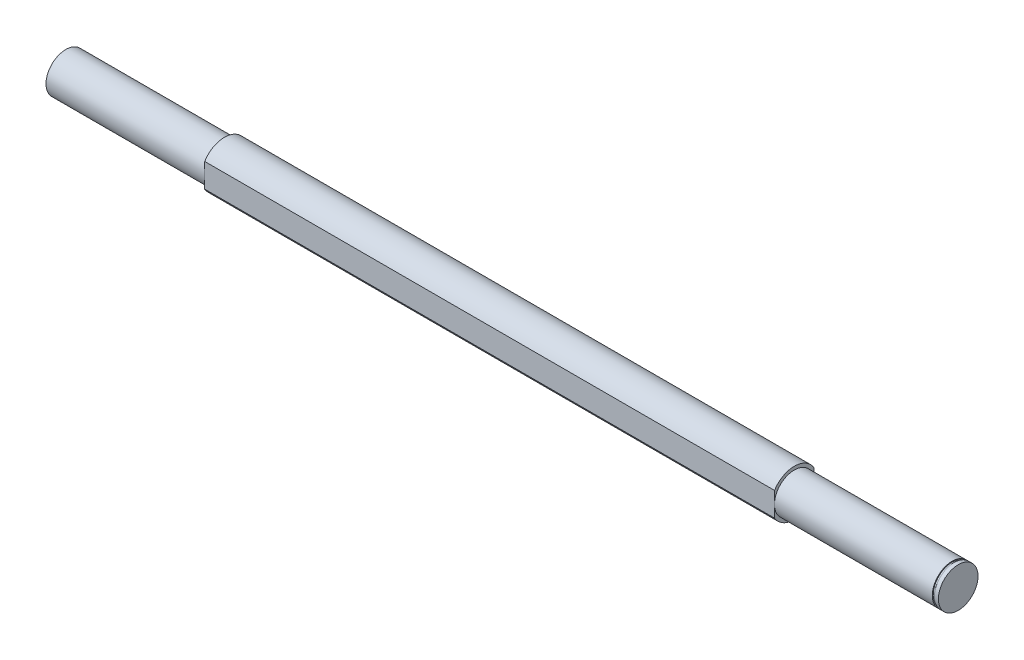
SolidWorks part; units mm, degrees
ref_plane "Ön Düzlem" through (0, 0, 0) normal (0, 0, 1) x (1, 0, 0)
ref_plane "Üst Düzlem" through (0, 0, 0) normal (0, 1, 0) x (1, 0, 0)
ref_plane "Sağ Düzlem" through (0, 0, 0) normal (1, 0, 0) x (0, 0, -1)
sketch "Sketch1" plane through (0, 0, 0) normal (0, 0, 1) x (1, 0, 0)
  line L0 (-337.5, 0) -> (337.5, 0)
  line L1 (-337.5, 0) -> (-337.5, 15)
  line L2 (-337.5, 15) -> (-217.5, 15)
  line L3 (-217.5, 15) -> (-217.5, 17.5)
  line L4 (-217.5, 17.5) -> (213.5, 17.5)
  line L5 (213.5, 17.5) -> (213.5, 15)
  line L6 (213.5, 15) -> (337.5, 15)
  line L7 (337.5, 15) -> (337.5, 0)
  point P4 (0, 0)
  dimension "D1" = 124
  dimension "D2" = 431
  dimension "D3" = 120
  dimension "D4" = 15
  dimension "D5" = 17.5
revolve "Revolve1" add sketch "Sketch1" angle 360 about L0
sketch "Sketch2" plane through (-217.5, 0, 0) normal (-1, 0, 0) x (0, 0, 1)
  line L0 (-14.9366, 9.1186) -> (-15.0627, -8.9088)
  line L1 (0, 0) -> (0, 5.213) construction
  line L2 (14.9366, 9.1186) -> (15.0627, -8.9088)
  circle A0 centre (0, 0) radius 15 construction
  circle A2 centre (0, 0) radius 17.5 construction
  arc A4 (-14.9366, 9.1186) -> (-15.0627, -8.9088) centre (0, 0) ccw
  arc A5 (14.9366, 9.1186) -> (15.0627, -8.9088) centre (0, 0) cw
extrude "Cut-Extrude1" cut sketch "Sketch2" against normal up to surface (431 mm away) up to face at (213.5, 0, 17.5)
ref_plane "Plane1" through (0, 0, -15) normal (0, 0, 1) x (1, 0, 0)
sketch "Sketch3" plane through (0, 0, -15) normal (0, 0, 1) x (1, 0, 0)
  line L0 (-331.5, 0) -> (-311.5, 0) construction
  line L1 (-331.5, 4) -> (-311.5, 4)
  line L2 (-331.5, -4) -> (-311.5, -4)
  line L3 (-337.5, 15) -> (-337.5, -15) construction
  arc A0 (-331.5, 4) -> (-331.5, -4) centre (-331.5, 0) ccw
  arc A1 (-311.5, -4) -> (-311.5, 4) centre (-311.5, 0) ccw
  point P3 (-321.5, 0)
  dimension "D1" = 8
  dimension "D2" = 6
  dimension "D3" = 20
extrude "Cut-Extrude2" cut sketch "Sketch3" along normal blind 4
sketch "Sketch4" plane through (0, 0, 0) normal (0, 0, 1) x (1, 0, 0)
  line L0 (337.5, 15) -> (213.5, 15) construction
  line L1 (332.9, 15) -> (334.5, 15)
  line L2 (332.9, 15) -> (332.9, 14.3)
  line L3 (332.9, 14.3) -> (334.5, 14.3)
  line L4 (334.5, 15) -> (334.5, 14.3)
  line L5 (337.5, 0) -> (329.1088, 0) construction
  line L6 (337.5, -15) -> (337.5, 15) construction
  dimension "D1" = 14.3
  dimension "D2" = 1.6
  dimension "D3" = 3
revolve "Cut-Revolve1" cut sketch "Sketch4" angle 360 about L5
sketch "Sketch5" plane through (0, 0, -15) normal (0, 0, 1) x (1, 0, 0)
  line L0 (324.5, 0) -> (289.5, 0) construction
  line L1 (324.5, -5) -> (289.5, -5)
  line L2 (324.5, 5) -> (289.5, 5)
  line L7 (332.9, 0) -> (213.5, 0) construction
  line L9 (337.5, -15) -> (337.5, 15) construction
  arc A0 (324.5, -5) -> (324.5, 5) centre (324.5, 0) ccw
  arc A1 (289.5, 5) -> (289.5, -5) centre (289.5, 0) ccw
  point P2 (307, 0)
  point P9 (329.5, 0)
  dimension "D1" = 10
  dimension "D2" = 8
  dimension "D3" = 35
extrude "Cut-Extrude3" cut sketch "Sketch5" along normal blind 5
